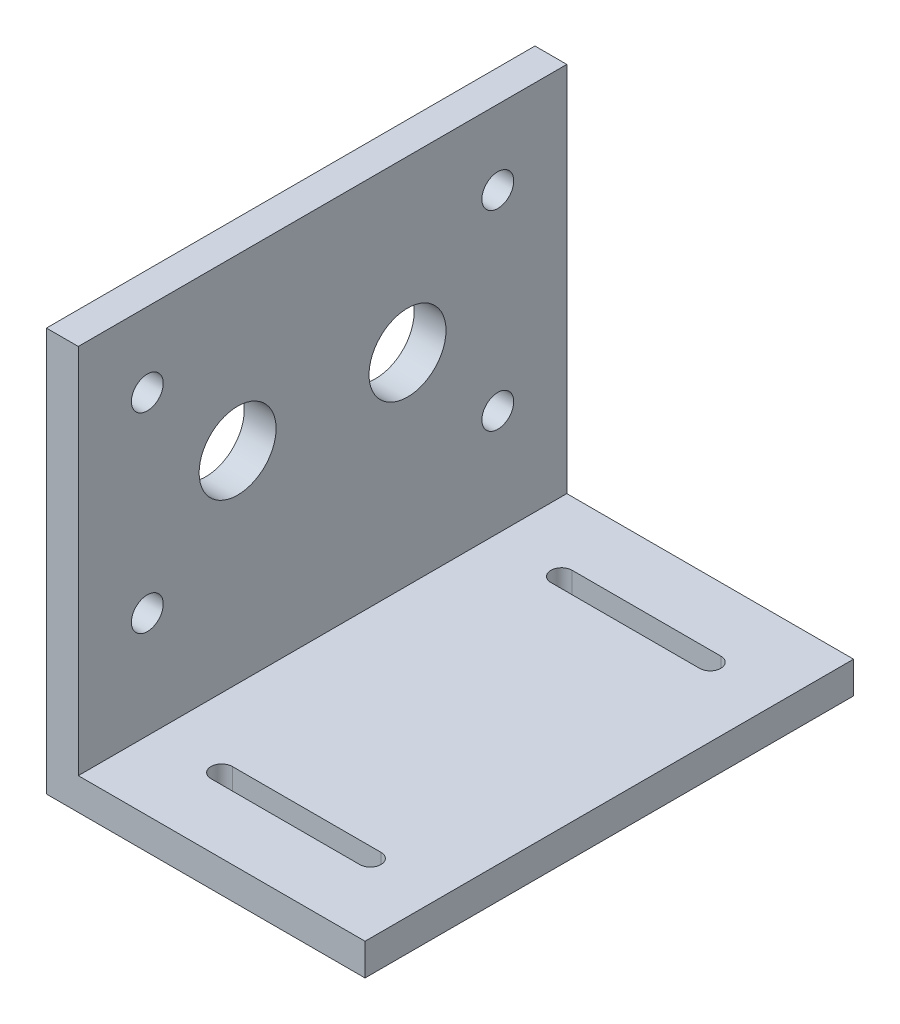
SolidWorks part; units mm, degrees
ref_plane "Front Plane" through (0, 0, 0) normal (0, 0, 1) x (1, 0, 0)
ref_plane "Top Plane" through (0, 0, 0) normal (0, 1, 0) x (1, 0, 0)
ref_plane "Right Plane" through (0, 0, 0) normal (1, 0, 0) x (0, 0, -1)
sketch "Sketch1" plane through (0, 0, 0) normal (0, 0, 1) x (1, 0, 0)
  line L0 (0, 0) -> (30, 0)
  line L1 (0, 0) -> (0, 38)
  line L2 (3, 3) -> (30, 3)
  line L3 (3, 3) -> (3, 38)
  line L4 (30, 0) -> (30, 3)
  line L5 (0, 38) -> (3, 38)
  dimension "D1" = 30
  dimension "D2" = 38
  dimension "D3" = 3
extrude "Boss-Extrude1" add sketch "Sketch1" along normal blind 46
sketch "Sketch2" plane through (3, 0, 0) normal (1, 0, 0) x (0, 0, -1)
  line L0 (-23, 38) -> (-23, 3) construction
  line L1 (-46, 38) -> (0, 38) construction
  line L2 (-46, 3) -> (0, 3) construction
  line L3 (-46, 20.5) -> (0, 20.5) construction
  line L4 (-46, 3) -> (-46, 38) construction
  line L5 (0, 3) -> (0, 38) construction
  line L6 (-46, 22) -> (0, 22) construction
  line L7 (-15, 38) -> (-15, 0) construction
  line L8 (-46, 0) -> (0, 0) construction
  circle A0 centre (-15, 22) radius 3.625
  circle A1 centre (-31, 22) radius 3.625
  dimension "D3" = 7.25
  dimension "D1" = 16
  dimension "D2" = 15
  dimension "D4" = 22
extrude "Cut-Extrude1" cut sketch "Sketch2" against normal blind 46
sketch "Sketch3" plane through (0, 0, 0) normal (-1, 0, 0) x (0, 0, 1)
  line L0 (23, 38) -> (23, 0) construction
  line L1 (46, 38) -> (0, 38) construction
  line L2 (46, 0) -> (0, 0) construction
  line L3 (0, 31) -> (46.3277, 31) construction
  line L4 (0, 38) -> (0, 0) construction
  line L7 (39.5, 38) -> (39.5, -1.0263) construction
  circle A0 centre (39.5, 31) radius 1.5
  circle A1 centre (6.5, 31) radius 1.5
  circle A2 centre (39.5, 13) radius 1.5
  circle A3 centre (6.5, 13) radius 1.5
  dimension "D3" = 3
  dimension "D1" = 18
  dimension "D2" = 16.5
  dimension "D4" = 7
  dimension "D5" = 18
extrude "Cut-Extrude2" cut sketch "Sketch3" against normal blind 10
sketch "Sketch4" plane through (0, 3, 0) normal (0, 1, 0) x (1, 0, 0)
  line L0 (3, -23) -> (30, -23) construction
  line L1 (3, -46) -> (3, 0) construction
  line L2 (30, -46) -> (30, 0) construction
  line L3 (3, -7) -> (30, -7) construction
  line L4 (16.5, 0) -> (16.5, -46) construction
  line L5 (30, 0) -> (3, 0) construction
  line L6 (30, -46) -> (3, -46) construction
  line L7 (9.5, -38) -> (23.5, -38)
  line L8 (9.5, -6) -> (23.5, -6)
  line L10 (9.5, -8) -> (23.5, -8)
  line L12 (9.5, -40) -> (23.5, -40)
  arc A0 (9.5, -6) -> (9.5, -8) centre (9.5, -7) ccw
  arc A1 (23.5, -6) -> (23.5, -8) centre (23.5, -7) cw
  arc A2 (23.5, -40) -> (23.5, -38) centre (23.5, -39) ccw
  arc A3 (9.5, -40) -> (9.5, -38) centre (9.5, -39) cw
  point P15 (16.5, -7)
  dimension "D3" = 2
  dimension "D1" = 16
  dimension "D2" = 14
extrude "Cut-Extrude3" cut sketch "Sketch4" against normal blind 10
